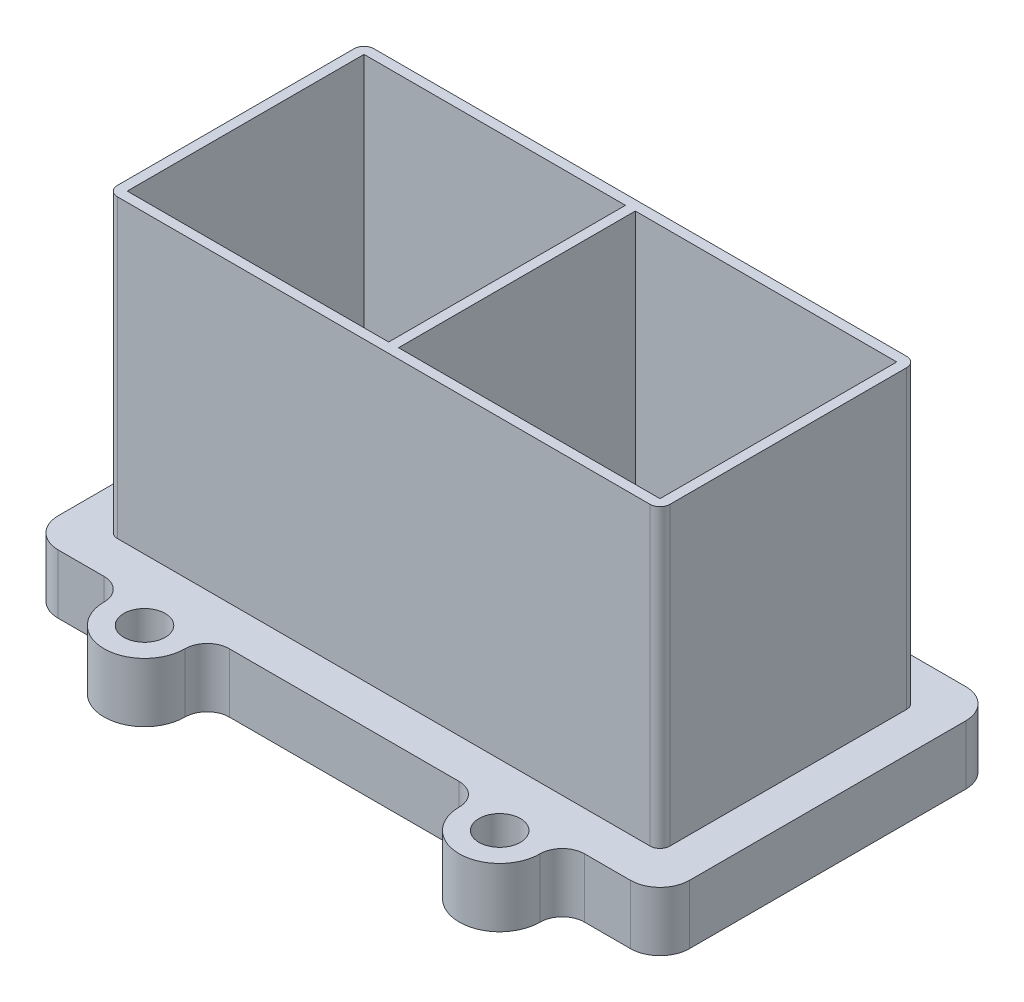
SolidWorks part; units mm, degrees
ref_plane "Front Plane" through (0, 0, 0) normal (0, 0, 1) x (1, 0, 0)
ref_plane "Top Plane" through (0, 0, 0) normal (0, 1, 0) x (1, 0, 0)
ref_plane "Right Plane" through (0, 0, 0) normal (1, 0, 0) x (0, 0, -1)
sketch "Base-plate and ports" plane through (0, 0, 0) normal (0, 1, 0) x (1, 0, 0)
  line L5 (-16, -7) -> (-16, 7)
  line L10 (-15, -7) -> (-15, 7)
  line L11 (-14.5, 7.5) -> (14.5, 7.5)
  line L12 (15, -7) -> (15, 7)
  line L13 (-14.5, -7.5) -> (14.5, -7.5)
  line L14 (16, -7) -> (16, 7)
  line L16 (-14.5, -8.5) -> (14.5, -8.5) construction
  line L17 (-14.5, 8.5) -> (14.5, 8.5) construction
  line L18 (-14.5, 8.5) -> (-3.175, 8.5)
  line L20 (3.175, 8.5) -> (14.5, 8.5)
  line L21 (12.175, -8.5) -> (14.5, -8.5)
  line L22 (5.825, -8.5) -> (-5.825, -8.5)
  line L23 (-12.175, -8.5) -> (-14.5, -8.5)
  circle A33 centre (-10.5, 3) radius 0.35
  circle A34 centre (0, 3) radius 0.35
  circle A35 centre (10.5, 3) radius 0.35
  circle A36 centre (0, -3) radius 0.35
  circle A37 centre (10.5, -3) radius 0.35
  circle A38 centre (-10.5, -3) radius 0.35
  arc A41 (-15, -7) -> (-14.5, -7.5) centre (-14.5, -7) ccw
  arc A42 (14.5, -7.5) -> (15, -7) centre (14.5, -7) ccw
  arc A43 (15, 7) -> (14.5, 7.5) centre (14.5, 7) ccw
  arc A44 (-14.5, 7.5) -> (-15, 7) centre (-14.5, 7) ccw
  circle A45 centre (0, 9.625) radius 1.05
  circle A46 centre (-9, -9.625) radius 1.05
  circle A47 centre (9, -9.625) radius 1.05
  arc A48 (-14.5, 8.5) -> (-16, 7) centre (-14.5, 7) ccw
  arc A49 (16, 7) -> (14.5, 8.5) centre (14.5, 7) ccw
  arc A50 (14.5, -8.5) -> (16, -7) centre (14.5, -7) ccw
  arc A51 (-16, -7) -> (-14.5, -8.5) centre (-14.5, -7) ccw
  arc A52 (-11.05, -9.625) -> (-6.95, -9.625) centre (-9, -9.625) ccw
  arc A53 (6.95, -9.625) -> (11.05, -9.625) centre (9, -9.625) ccw
  arc A54 (-2.05, 9.625) -> (2.05, 9.625) centre (0, 9.625) cw
  arc A55 (-11.05, -9.625) -> (-12.175, -8.5) centre (-12.175, -9.625) ccw
  arc A56 (-6.95, -9.625) -> (-5.825, -8.5) centre (-5.825, -9.625) cw
  arc A57 (6.95, -9.625) -> (5.825, -8.5) centre (5.825, -9.625) ccw
  arc A58 (11.05, -9.625) -> (12.175, -8.5) centre (12.175, -9.625) cw
  arc A59 (2.05, 9.625) -> (3.175, 8.5) centre (3.175, 9.625) ccw
  arc A60 (-2.05, 9.625) -> (-3.175, 8.5) centre (-3.175, 9.625) cw
  point P2 (-15, -7.5)
  point P5 (0, 7.5)
  point P10 (15, 7.5)
  point P16 (-15, 7.5)
  point P17 (-15, 0)
  dimension "D7" = 30
  dimension "D3" = 6
  dimension "D8" = 10.5
  dimension "D9" = 0.5
  dimension "D10" = 0.7
  dimension "D18" = 1
  dimension "D19" = 4.1
  dimension "D5" = 4.5
  dimension "D12" = 2.125
  dimension "D13" = 2.125
  dimension "D11" = 2.1
  dimension "D2" = 4.5
  dimension "D6" = 10.5
  dimension "D4" = 15
  dimension "D16" = 2
  dimension "D17" = 18
  dimension "D14" = 6
  dimension "D15" = 3
extrude "Base plate and ports" add sketch "Base-plate and ports" along normal mid plane 3
sketch "Reservoirs" plane through (0, 1.5, 0) normal (0, 1, 0) x (1, 0, 0)
  line L0 (-15, -7) -> (-15, 7) construction
  line L1 (-13.5, -6.5) -> (13.5, -6.5)
  line L2 (-14, -6) -> (-14, 6)
  line L3 (-13.5, 6.5) -> (13.5, 6.5)
  line L4 (14, -6) -> (14, 6)
  line L5 (-14, -6.5) -> (14, 6.5) construction
  line L6 (-14, 6.5) -> (14, -6.5) construction
  line L7 (-14.5, 7.5) -> (14.5, 7.5) construction
  line L8 (-4.3333, -6) -> (4.3333, -6)
  line L9 (-13.5, -6) -> (-4.8333, -6)
  line L10 (-13.5, -6) -> (-13.5, 6)
  line L11 (-13.5, 6) -> (-4.8333, 6)
  line L12 (-4.8333, -6) -> (-4.8333, 6)
  line L13 (-13.5, -6) -> (-4.8333, 6) construction
  line L14 (-13.5, 6) -> (-4.8333, -6) construction
  line L15 (-4.3333, -6) -> (-4.3333, 6)
  line L16 (-4.3333, 6) -> (4.3333, 6)
  line L17 (4.3333, -6) -> (4.3333, 6)
  line L18 (-4.3333, -6) -> (4.3333, 6) construction
  line L19 (-4.3333, 6) -> (4.3333, -6) construction
  line L20 (4.8333, -6) -> (13.5, -6)
  line L21 (4.8333, -6) -> (4.8333, 6)
  line L22 (4.8333, 6) -> (13.5, 6)
  line L23 (13.5, -6) -> (13.5, 6)
  line L24 (4.8333, -6) -> (13.5, 6) construction
  line L25 (4.8333, 6) -> (13.5, -6) construction
  line L26 (-4.8333, 6) -> (-4.3333, 6)
  line L27 (-0.25, 6) -> (0.25, 6)
  line L28 (-0.25, 6) -> (-0.25, -6)
  line L29 (-0.25, -6) -> (0.25, -6)
  line L30 (0.25, 6) -> (0.25, -6)
  line L31 (4.3333, 6) -> (4.8333, 6)
  line L32 (-4.8333, -6) -> (-4.3333, -6)
  line L33 (4.3333, -6) -> (4.8333, -6)
  arc A0 (-14, -6) -> (-13.5, -6.5) centre (-13.5, -6) ccw
  arc A1 (13.5, -6.5) -> (14, -6) centre (13.5, -6) ccw
  arc A2 (14, 6) -> (13.5, 6.5) centre (13.5, 6) ccw
  arc A3 (-13.5, 6.5) -> (-14, 6) centre (-13.5, 6) ccw
  point P0 (0, 0)
  point P10 (-9.1667, 0)
  point P16 (9.1667, 0)
  point P18 (0, 0)
  point P41 (0, 6)
  dimension "D10" = 0.5
  dimension "D1" = 1
  dimension "D2" = 1
  dimension "D3" = 0.5
  dimension "D4" = 0.5
  dimension "D5" = 0.5
  dimension "D6" = 0.5
  dimension "D7" = 0.5
  dimension "D8" = 0.5
  dimension "D9" = 0.5
  dimension "D11" = 0.5
extrude "Boss-Extrude1" add sketch "Reservoirs" along normal blind 15 contours L3 A3 L2 A0 L1 A1 L4 A2 L33 L8 L32 L9 L10 L11 L26 L16 L31 L22 L23 L20 | L30 L29 L28 L27
